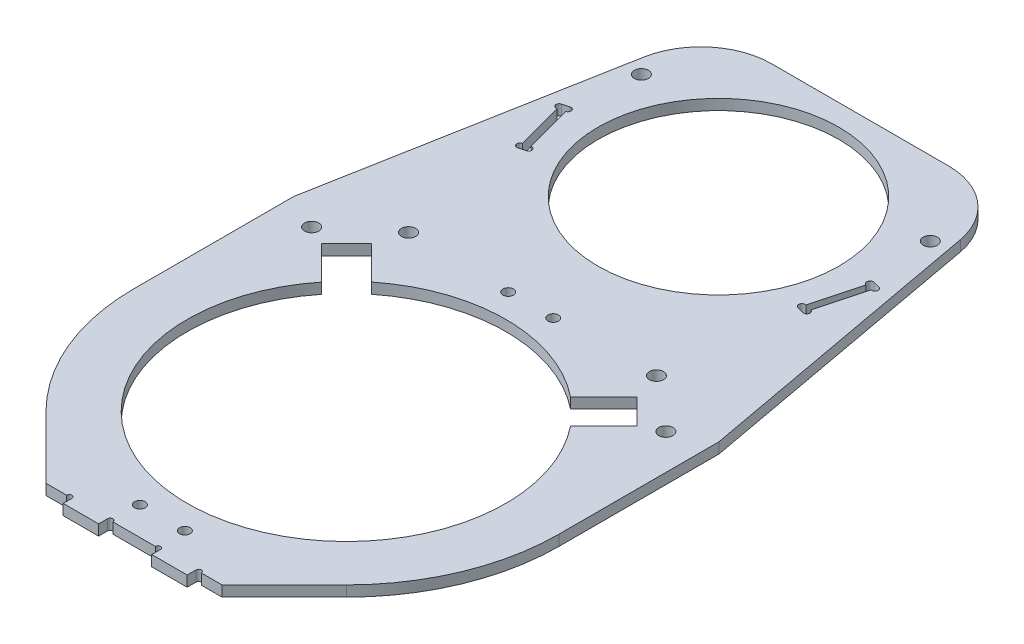
SolidWorks part; units mm, degrees
material "Thornel Mat VMA"
ref_plane "前视基准面" through (0, 0, 0) normal (0, 0, 1) x (1, 0, 0)
ref_plane "上视基准面" through (0, 0, 0) normal (0, 1, 0) x (1, 0, 0)
ref_plane "右视基准面" through (0, 0, 0) normal (1, 0, 0) x (0, 0, -1)
sketch "草图1" plane through (0, 0, 0) normal (0, 1, 0) x (1, 0, 0)
  line L8 (-6.35, 52) -> (-6.35, -52) construction
  line L9 (-6.35, 52) -> (6.35, 52) construction
  line L10 (-6.35, -52) -> (6.35, -52) construction
  line L17 (6.35, -52) -> (6.35, 52) construction
  line L18 (-78, 0) -> (78, 0) construction
  line L19 (0, 145) -> (0, -145) construction
  line L21 (24.8528, 60) -> (-24.8528, 60) construction
  line L22 (-24.8528, 60) -> (-60, 24.8528) construction
  line L23 (-60, 24.8528) -> (-60, -24.8528)
  line L24 (-60, -24.8528) -> (-24.8528, -60)
  line L25 (-24.8528, -60) -> (24.8528, -60)
  line L26 (24.8528, -60) -> (60, -24.8528)
  line L27 (60, -24.8528) -> (60, 24.8528)
  line L28 (60, 24.8528) -> (24.8528, 60) construction
  line L29 (-60, 24.8528) -> (-60, 45.1472)
  line L31 (60, 45.1472) -> (60, 24.8528)
  line L32 (-60, 45.1472) -> (-44.671, 128.6127)
  line L35 (44.671, 128.6127) -> (60, 45.1472)
  line L36 (-25, 145) -> (25, 145)
  circle A1 centre (-6.35, 52) radius 1.5
  circle A2 centre (6.35, 52) radius 1.5
  circle A3 centre (6.35, -52) radius 1.5
  circle A4 centre (-6.35, -52) radius 1.5
  circle A6 centre (0, 0) radius 45
  circle A7 centre (0, 0) radius 60 construction
  arc A10 (44.671, 128.6127) -> (25, 145) centre (25, 125) ccw
  arc A11 (-44.671, 128.6127) -> (-25, 145) centre (-25, 125) cw
  point P6 (-6.35, 0)
  point P7 (6.35, 0)
  point P10 (0, 52)
  point P15 (0, -52)
  dimension "D3" = 3
  dimension "D2" = 120
  dimension "D8" = 45
  dimension "D7" = 20
  dimension "D6" = 145
  dimension "D1" = 104
  dimension "D4" = 70
  dimension "D5" = 12.7
  dimension "D9" = 50
extrude "凸台-拉伸1" add sketch "草图1" along normal blind 3
sketch "草图2" plane through (0, 3, 0) normal (0, 1, 0) x (1, 0, 0)
  line L0 (0, 105) -> (0, 0) construction
  line L1 (0, 0) -> (27.0762, 0) construction
  line L2 (-35, 52.5) -> (35, 52.5) construction
  line L7 (-25.3256, -54.6087) -> (-20.7062, -56.5221) construction
  line L8 (28.0872, 35.1583) -> (35.1583, 28.0872)
  line L9 (35.1583, 28.0872) -> (44.5477, 37.4767)
  line L10 (28.0872, 35.1583) -> (37.4767, 44.5477)
  line L11 (37.4767, 44.5477) -> (44.5477, 37.4767)
  line L12 (0, 0) -> (41.0122, 41.0122) construction
  line L13 (-37.4767, 44.5477) -> (-44.5477, 37.4767)
  line L14 (-28.0872, 35.1583) -> (-37.4767, 44.5477)
  line L15 (-35.1583, 28.0872) -> (-44.5477, 37.4767)
  line L16 (-28.0872, 35.1583) -> (-35.1583, 28.0872)
  line L17 (-28.0872, -35.1583) -> (-35.1583, -28.0872) construction
  line L18 (-35.1583, -28.0872) -> (-44.5477, -37.4767) construction
  line L19 (-28.0872, -35.1583) -> (-37.4767, -44.5477) construction
  line L20 (-37.4767, -44.5477) -> (-44.5477, -37.4767) construction
  line L21 (37.4767, -44.5477) -> (44.5477, -37.4767) construction
  line L22 (28.0872, -35.1583) -> (37.4767, -44.5477) construction
  line L23 (35.1583, -28.0872) -> (44.5477, -37.4767) construction
  line L24 (28.0872, -35.1583) -> (35.1583, -28.0872) construction
  line L25 (-24.9812, -53.7772) -> (-20.3618, -55.6906) construction
  line L26 (-25.67, -55.4402) -> (-21.0506, -57.3536) construction
  line L27 (-24.8528, -60) -> (24.8528, -60) construction
  line L28 (-23.0159, -55.5654) -> (-24.8528, -60) construction
  line L29 (25.3256, -54.6087) -> (20.7062, -56.5221) construction
  line L30 (24.9812, -53.7772) -> (20.3618, -55.6906) construction
  line L31 (25.67, -55.4402) -> (21.0506, -57.3536) construction
  line L32 (-56.5221, -20.7062) -> (-54.6087, -25.3256) construction
  line L33 (-55.6906, -20.3618) -> (-53.7772, -24.9812) construction
  line L34 (-57.3536, -21.0506) -> (-55.4402, -25.67) construction
  line L35 (0, 0) -> (-25.3256, -54.6087) construction
  line L36 (0, 0) -> (-56.5221, -20.7062) construction
  line L37 (56.5221, -20.7062) -> (54.6087, -25.3256) construction
  line L38 (55.6906, -20.3618) -> (53.7772, -24.9812) construction
  line L39 (57.3536, -21.0506) -> (55.4402, -25.67) construction
  line L40 (0, 105) -> (40.7839, 124.0178) construction
  circle A12 centre (0, 105) radius 34
  circle A33 centre (-35, 52.5) radius 2
  circle A34 centre (0, 0) radius 45 construction
  circle A35 centre (35, 52.5) radius 2
  arc A36 (-24.9812, -53.7772) -> (-25.67, -55.4402) centre (-25.3256, -54.6087) ccw construction
  arc A37 (-21.0506, -57.3536) -> (-20.3618, -55.6906) centre (-20.7062, -56.5221) ccw construction
  arc A38 (24.9812, -53.7772) -> (25.67, -55.4402) centre (25.3256, -54.6087) cw construction
  arc A39 (21.0506, -57.3536) -> (20.3618, -55.6906) centre (20.7062, -56.5221) cw construction
  arc A40 (-55.6906, -20.3618) -> (-57.3536, -21.0506) centre (-56.5221, -20.7062) ccw construction
  arc A41 (-55.4402, -25.67) -> (-53.7772, -24.9812) centre (-54.6087, -25.3256) ccw construction
  arc A42 (55.6906, -20.3618) -> (57.3536, -21.0506) centre (56.5221, -20.7062) cw construction
  arc A43 (55.4402, -25.67) -> (53.7772, -24.9812) centre (54.6087, -25.3256) cw construction
  circle A44 centre (40.7839, 124.0178) radius 2
  circle A45 centre (-40.7839, 124.0178) radius 2
  circle A48 centre (-50, 40.1472) radius 2
  circle A49 centre (50, 40.1472) radius 2
  point P3 (0, 52.5)
  point P5 (0, 52.5)
  point P10 (-23.0159, -55.5654)
  point P28 (23.0159, -55.5654)
  point P35 (-55.5654, -23.0159)
  point P45 (55.5654, -23.0159)
  dimension "D3" = 4
  dimension "D4" = 70
  dimension "D5" = 1.8
  dimension "D6" = 5
  dimension "D7" = 22.5
  dimension "D9" = 4.8
  dimension "D11" = 68
  dimension "D18" = 4
  dimension "D23" = 50
  dimension "D24" = 4
  dimension "D25" = 5
  dimension "D12" = 105
  dimension "D13" = 45
  dimension "D14" = 58
  dimension "D15" = 10
  dimension "D17" = 45
  dimension "D19" = 115
  dimension "D20" = 45
  dimension "D16" = 2
extrude "切除-拉伸1" cut sketch "草图2" against normal through all
sketch "草图3" plane through (0, 0, 60) normal (0, 0, 1) x (1, 0, 0)
  line L0 (-24.8528, 3) -> (24.8528, 3) construction
  line L1 (-17.5, 3) -> (-7.5, 3)
  line L2 (-17.5, 3) -> (-17.5, 0)
  line L3 (-17.5, 0) -> (-7.5, 0)
  line L4 (-7.5, 3) -> (-7.5, 0)
  line L5 (-24.8528, 0) -> (24.8528, 0) construction
  line L6 (0, -1.65) -> (0, 1.65) construction
  line L7 (7.5, 3) -> (7.5, 0)
  line L8 (17.5, 0) -> (7.5, 0)
  line L9 (17.5, 3) -> (17.5, 0)
  line L10 (17.5, 3) -> (7.5, 3)
  dimension "D1" = 15
  dimension "D2" = 10
extrude "凸台-拉伸2" add sketch "草图3" along normal blind 2.5
sketch "草图5" plane through (0, 3, 0) normal (0, 1, 0) x (1, 0, 0)
  line L0 (0, 71) -> (0, 60) construction
  line L1 (0, 145) -> (0, -145) construction
  line L2 (24.8528, 60) -> (-24.8528, 60) construction
  line L3 (0, 0) -> (-39.8364, 148.6714) construction
  line L7 (-24.8528, -60) -> (-17.5, -60) construction
  line L8 (-7.5, -60) -> (7.5, -60) construction
  line L9 (17.5, -60) -> (24.8528, -60) construction
  line L13 (0, -1.65) -> (0, 1.65) construction
  line L18 (-44.7942, 105.5013) -> (-40.2648, 88.5976)
  line L19 (-44.7942, 105.5013) -> (-42.8623, 106.0189)
  line L20 (-40.2648, 88.5976) -> (-38.333, 89.1152)
  line L21 (-42.8623, 106.0189) -> (-38.333, 89.1152)
  line L23 (42.8623, 106.0189) -> (38.333, 89.1152)
  line L24 (40.2648, 88.5976) -> (38.333, 89.1152)
  line L25 (44.7942, 105.5013) -> (42.8623, 106.0189)
  line L26 (44.7942, 105.5013) -> (40.2648, 88.5976)
  line L36 (-60, 45.1472) -> (-60, -24.8528) construction
  line L37 (-60, -24.8528) -> (-24.8528, -60) construction
  line L38 (-60, 0) -> (-60, -24.8528)
  line L42 (-60, -24.8528) -> (-42.4264, -42.4264)
  line L43 (60, -24.8528) -> (42.4264, -42.4264)
  line L44 (60, 0) -> (60, -24.8528)
  circle A0 centre (0, 105) radius 34 construction
  circle A7 centre (-18.25, -60) radius 0.75
  circle A8 centre (-6.75, -60) radius 0.75
  circle A9 centre (6.75, -60) radius 0.75
  circle A10 centre (18.25, -60) radius 0.75
  arc A37 (-60, 0) -> (-42.4264, -42.4264) centre (0, 0) ccw
  arc A38 (60, 0) -> (42.4264, -42.4264) centre (0, 0) cw
  dimension "D3" = 1.5
  dimension "D4" = 96
  dimension "D11" = 120
  dimension "D2" = 2
  dimension "D5" = 17.5
  dimension "D6" = 13.9621
  dimension "D8" = 15
extrude "切除-拉伸2" cut sketch "草图5" against normal through all
sketch "草图8" plane through (0, 3, 0) normal (0, 1, 0) x (1, 0, 0)
  line L18 (0, -1.65) -> (0, 1.65) construction
  line L42 (-44.7942, 105.5013) -> (-40.2648, 88.5976) construction
  line L43 (-38.333, 89.1152) -> (-42.8623, 106.0189) construction
  circle A69 centre (-44.5612, 104.6319) radius 0.9
  circle A70 centre (-42.6294, 105.1496) radius 0.9
  circle A71 centre (-38.5659, 89.9846) radius 0.9
  circle A72 centre (-40.4978, 89.4669) radius 0.9
  circle A73 centre (40.4978, 89.4669) radius 0.9
  circle A74 centre (38.5659, 89.9846) radius 0.9
  circle A75 centre (42.6294, 105.1496) radius 0.9
  circle A76 centre (44.5612, 104.6319) radius 0.9
  dimension "D1" = 1.8
extrude "切除-拉伸3" cut sketch "草图8" against normal through all
sketch "草图9" [suppressed] plane through (0, 3, 0) normal (0, 1, 0) x (1, 0, 0)
  line L0 (-67.5, 27) -> (-110, 56)
  line L1 (-110, 27) -> (-67.5, 56)
  line L2 (-107.5, 9) -> (-62.5, -9)
  line L3 (-107.5, -9) -> (-62.5, 9)
  line L5 (92.5, 17) -> (62.5, -1)
  line L7 (110, 27) -> (67.5, 49.0204)
  line L8 (67.5, 27) -> (110, 49.0204)
extrude "拉伸-薄壁1" [suppressed] add sketch "草图9" against normal up to surface (3 mm away) thin
sketch "草图10" [suppressed] plane through (0, 3, 0) normal (0, 1, 0) x (1, 0, 0)
  line L0 (-135, 65.8183) -> (-57.2183, 143.6001)
  line L1 (-57.2183, 143.6001) -> (-54.1292, 140.511)
  line L2 (-78.4116, 122.4067) -> (-135, 65.8183) construction
  line L3 (-135, 65.8183) -> (-54.1292, 140.511)
  line L4 (0, -1.65) -> (0, 1.65) construction
  line L5 (135, 65.8183) -> (57.2183, 143.6001)
  line L6 (57.2183, 143.6001) -> (54.1292, 140.511)
  line L7 (135, 65.8183) -> (54.1292, 140.511)
  arc A0 (-15.4534, 152.552) -> (-78.4116, 122.4067) centre (-4.1654, 48.1605) ccw construction
  dimension "D1" = 110
extrude "凸台-拉伸5" [suppressed] add sketch "草图10" against normal blind 3
sketch "草图11" [suppressed] plane through (0, 3, 0) normal (0, 1, 0) x (1, 0, 0)
  line L0 (-57.2183, 143.6001) -> (-71.3604, 129.4579)
  line L1 (-57.2183, 143.6001) -> (-59.3396, 145.7214)
  line L2 (-71.3604, 129.4579) -> (-73.4817, 131.5793)
  line L3 (-59.3396, 145.7214) -> (-73.4817, 131.5793)
  line L4 (-57.2183, 143.6001) -> (-135, 65.8183) construction
  line L5 (-135, 65.8183) -> (-120.9286, 79.8898)
  line L6 (-135, 65.8183) -> (-137.1213, 67.9396)
  line L7 (-120.9286, 79.8898) -> (-123.0499, 82.0111)
  line L8 (-137.1213, 67.9396) -> (-123.0499, 82.0111)
  line L9 (-99.7154, 101.103) -> (-82.0377, 118.7806)
  line L10 (-99.7154, 101.103) -> (-101.8367, 103.2243)
  line L11 (-82.0377, 118.7806) -> (-84.159, 120.9019)
  line L12 (-101.8367, 103.2243) -> (-84.159, 120.9019)
  line L13 (0, -1.65) -> (0, 1.65) construction
  line L14 (101.8367, 103.2243) -> (84.159, 120.9019)
  line L15 (82.0377, 118.7806) -> (84.159, 120.9019)
  line L16 (99.7154, 101.103) -> (101.8367, 103.2243)
  line L17 (99.7154, 101.103) -> (82.0377, 118.7806)
  line L18 (137.1213, 67.9396) -> (123.0499, 82.0111)
  line L19 (120.9286, 79.8898) -> (123.0499, 82.0111)
  line L20 (135, 65.8183) -> (137.1213, 67.9396)
  line L21 (135, 65.8183) -> (120.9286, 79.8898)
  line L22 (59.3396, 145.7214) -> (73.4817, 131.5793)
  line L23 (71.3604, 129.4579) -> (73.4817, 131.5793)
  line L24 (57.2183, 143.6001) -> (59.3396, 145.7214)
  line L25 (57.2183, 143.6001) -> (71.3604, 129.4579)
  dimension "D1" = 3
  dimension "D2" = 20
  dimension "D3" = 19.9
  dimension "D4" = 15.1
  dimension "D5" = 30
extrude "凸台-拉伸6" [suppressed] add sketch "草图11" against normal blind 3
sketch "草图12" [suppressed] plane through (0, 3, 0) normal (0, 1, 0) x (1, 0, 0)
  line L0 (-97.5, 40.8183) -> (-97.5, 44.8183) construction
  line L5 (-135, 40.8183) -> (-60, 40.8183) construction
  line L6 (0, -1.65) -> (0, 1.65) construction
  line L7 (-112.5, 45.8183) -> (-82.5, 45.8183)
  line L8 (-112.5, 45.8183) -> (-112.5, 43.8183)
  line L9 (-112.5, 43.8183) -> (-82.5, 43.8183)
  line L10 (-82.5, 45.8183) -> (-82.5, 43.8183)
  line L11 (-112.5, 45.8183) -> (-82.5, 43.8183) construction
  line L12 (-112.5, 43.8183) -> (-82.5, 45.8183) construction
  line L13 (112.5, 43.8183) -> (82.5, 43.8183)
  line L14 (82.5, 45.8183) -> (82.5, 43.8183)
  line L15 (112.5, 45.8183) -> (82.5, 45.8183)
  line L16 (112.5, 45.8183) -> (112.5, 43.8183)
  dimension "D1" = 3
  dimension "D2" = 2
  dimension "D3" = 30
extrude "切除-拉伸4" [suppressed] cut sketch "草图12" against normal blind 10
sketch "草图13" [suppressed] plane through (0, 3, 0) normal (0, 1, 0) x (1, 0, 0)
  line L0 (-71.3604, 129.4579) -> (-82.0377, 118.7806) construction
  line L1 (-99.7154, 101.103) -> (-120.9286, 79.8898) construction
  line L2 (-82.5, 45.8183) -> (-112.5, 45.8183) construction
  line L3 (-112.5, 43.8183) -> (-82.5, 43.8183) construction
  line L4 (0, -1.65) -> (0, 1.65) construction
  circle A0 centre (-71.9968, 128.8215) radius 0.9
  circle A1 centre (-81.4013, 119.417) radius 0.9
  circle A2 centre (-100.3518, 100.4666) radius 0.9
  circle A3 centre (-120.2922, 80.5261) radius 0.9
  circle A4 centre (-111.6, 45.8183) radius 0.9
  circle A5 centre (-111.6, 43.8183) radius 0.9
  circle A6 centre (-83.4, 45.8183) radius 0.9
  circle A7 centre (-83.4, 43.8183) radius 0.9
  circle A8 centre (83.4, 43.8183) radius 0.9
  circle A9 centre (83.4, 45.8183) radius 0.9
  circle A10 centre (111.6, 43.8183) radius 0.9
  circle A11 centre (111.6, 45.8183) radius 0.9
  circle A12 centre (120.2922, 80.5261) radius 0.9
  circle A13 centre (100.3518, 100.4666) radius 0.9
  circle A14 centre (81.4013, 119.417) radius 0.9
  circle A15 centre (71.9968, 128.8215) radius 0.9
  dimension "D1" = 1.8
extrude "切除-拉伸5" [suppressed] cut sketch "草图13" against normal through all
